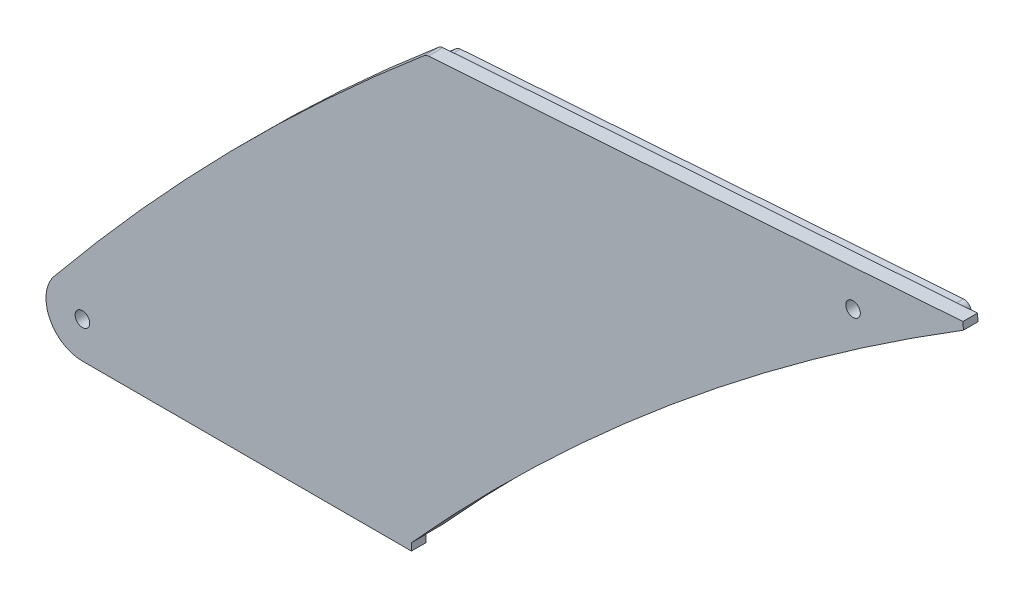
SolidWorks part; units mm, degrees
ref_plane "Front Plane" through (0, 0, 0) normal (0, 0, 1) x (1, 0, 0)
ref_plane "Top Plane" through (0, 0, 0) normal (0, 1, 0) x (1, 0, 0)
ref_plane "Right Plane" through (0, 0, 0) normal (1, 0, 0) x (0, 0, -1)
sketch "Sketch6" plane through (0, 0, 2) normal (0, 0, 1) x (1, 0, 0)
  line L0 (-47.1688, -59) -> (-2.4436, -59) construction
  line L1 (69.7935, 3.878) -> (0.7233, -0.9519) construction
  line L2 (-47.1688, -59) -> (-2.4436, -59)
  line L3 (69.7935, 3.878) -> (0.7233, -0.9519)
  line L4 (-47.1688, -58) -> (-2.4436, -58)
  line L5 (69.8632, 2.8804) -> (0.793, -1.9494)
  arc A0 (-2.4436, -59) -> (-1.7027, -58.6716) centre (-2.4436, -58) ccw construction
  arc A1 (-50.2623, -52.4643) -> (-47.1688, -59) centre (-47.1688, -55) ccw construction
  arc A2 (73.7864, 4.1572) -> (-2, -59) centre (258.3719, -294.388) ccw construction
  arc A3 (70.3988, 2.0359) -> (69.7935, 3.878) centre (69.8632, 2.8804) ccw construction
  arc A4 (0.7233, -0.9519) -> (0.146, -1.187) centre (0.793, -1.9494) ccw construction
  arc A5 (0.146, -1.187) -> (-50.2623, -52.4643) centre (258.3207, -305.4021) ccw construction
  arc A6 (-2.4436, -59) -> (-1.7027, -58.6716) centre (-2.4436, -58) ccw
  arc A7 (-50.2623, -52.4643) -> (-47.1688, -59) centre (-47.1688, -55) ccw
  arc A8 (70.3988, 2.0359) -> (-1.7027, -58.6716) centre (258.3719, -294.388) ccw
  arc A9 (70.3988, 2.0359) -> (69.7935, 3.878) centre (69.8632, 2.8804) ccw
  arc A10 (0.7233, -0.9519) -> (0.146, -1.187) centre (0.793, -1.9494) ccw
  arc A11 (0.146, -1.187) -> (-50.2623, -52.4643) centre (258.3207, -305.4021) ccw
  arc A12 (69.8632, 2.8804) -> (-2.4436, -58) centre (258.3719, -294.388) ccw
  arc A13 (-2.4436, -58) -> (-2.4436, -58) centre (-2.4436, -58) ccw
  arc A14 (-49.4889, -53.0982) -> (-47.1688, -58) centre (-47.1688, -55) ccw
  arc A15 (0.793, -1.9494) -> (-49.4889, -53.0982) centre (258.3207, -305.4021) ccw
  arc A16 (0.793, -1.9494) -> (0.793, -1.9494) centre (0.793, -1.9494) ccw
  arc A17 (69.8632, 2.8804) -> (69.8632, 2.8804) centre (69.8632, 2.8804) ccw
  dimension "D1" = 1
extrude "Boss-Extrude2" add sketch "Sketch6" along normal blind 2
sketch "Sketch7" plane through (0, 0, 4) normal (0, 0, 1) x (1, 0, 0)
  line L0 (73.7167, 5.1548) -> (0.3265, 0.0228) construction
  line L1 (73.7864, 4.1572) -> (73.7167, 5.1548) construction
  line L2 (-2, -59) -> (-2, -60) construction
  line L3 (-47.1688, -60) -> (-2, -60) construction
  line L4 (73.7167, 5.1548) -> (0.3265, 0.0228)
  line L5 (73.7864, 4.1572) -> (73.7167, 5.1548)
  line L6 (-2, -59) -> (-2, -60)
  line L7 (-47.1688, -60) -> (-2, -60)
  arc A0 (0.3265, 0.0228) -> (-0.2501, -0.2118) centre (0.3963, -0.9747) ccw construction
  arc A1 (73.7864, 4.1572) -> (-2, -59) centre (258.3719, -294.388) ccw construction
  arc A2 (-51.0357, -51.8304) -> (-47.1688, -60) centre (-47.1688, -55) ccw construction
  arc A3 (-0.2501, -0.2118) -> (-51.0357, -51.8304) centre (258.3207, -305.4021) ccw construction
  arc A4 (0.3265, 0.0228) -> (-0.2501, -0.2118) centre (0.3963, -0.9747) ccw
  arc A5 (73.7864, 4.1572) -> (-2, -59) centre (258.3719, -294.388) ccw
  arc A6 (-51.0357, -51.8304) -> (-47.1688, -60) centre (-47.1688, -55) ccw
  arc A7 (-0.2501, -0.2118) -> (-51.0357, -51.8304) centre (258.3207, -305.4021) ccw
  circle A8 centre (58.6292, -0.9125) radius 1 construction
  circle A9 centre (-47.1688, -55) radius 1 construction
  circle A10 centre (58.6292, -0.9125) radius 1
  circle A11 centre (-47.1688, -55) radius 1
extrude "Boss-Extrude3" add sketch "Sketch7" along normal blind 2
fillet "Fillet1" radius 2 3 edges at (-2.4436, -58, 3) (0.793, -1.9494, 3) (69.8632, 2.8804, 3)
